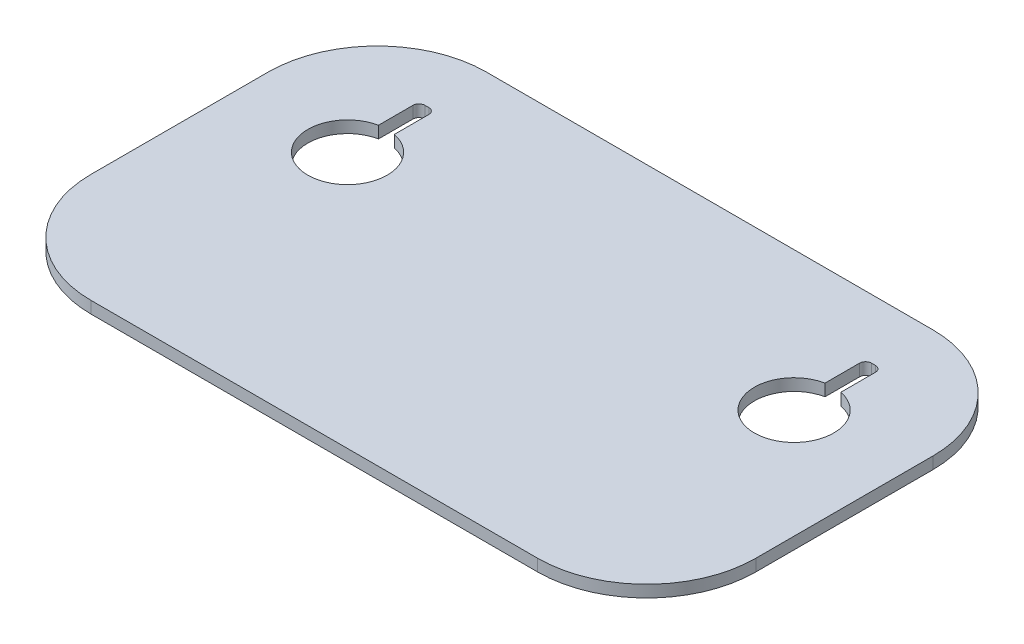
SolidWorks part; units mm, degrees
ref_plane "Front Plane" through (0, 0, 0) normal (0, 0, 1) x (1, 0, 0)
ref_plane "Top Plane" through (0, 0, 0) normal (0, 1, 0) x (1, 0, 0)
ref_plane "Right Plane" through (0, 0, 0) normal (1, 0, 0) x (0, 0, -1)
sketch "Sketch1" plane through (0, 0, 0) normal (0, 1, 0) x (1, 0, 0)
  line L1 (-9.9666, 27.987) -> (215.0634, 27.987)
  line L2 (-64.9666, -27.013) -> (-64.9666, -116.273)
  line L3 (-9.9666, -171.273) -> (215.0634, -171.273)
  line L4 (270.0634, -27.013) -> (270.0634, -116.273)
  arc A0 (-64.9666, -116.273) -> (-9.9666, -171.273) centre (-9.9666, -116.273) ccw
  arc A1 (215.0634, -171.273) -> (270.0634, -116.273) centre (215.0634, -116.273) ccw
  arc A2 (215.0634, 27.987) -> (270.0634, -27.013) centre (215.0634, -27.013) cw
  arc A3 (-9.9666, 27.987) -> (-64.9666, -27.013) centre (-9.9666, -27.013) ccw
  dimension "D3" = 55
extrude "Boss-Extrude1" add sketch "Sketch1" along normal blind 6
sketch "Sketch3" plane through (0, 6, 0) normal (0, 1, 0) x (1, 0, 0)
  line L0 (-9.9666, 53.1042) -> (-9.9666, -2.013) construction
  line L1 (215.0634, 48.0234) -> (215.0634, -218.0505) construction
  line L2 (-64.9666, -27.013) -> (-64.9666, -116.273) construction
  line L3 (270.0634, -116.273) -> (270.0634, -27.013) construction
  line L4 (-115.6589, -42.013) -> (-13.9666, -42.013) construction
  line L5 (215.0634, 27.987) -> (-9.9666, 27.987) construction
  line L6 (10.0334, -42.013) -> (321.2905, -42.013) construction
  line L7 (-10.9666, -2.013) -> (-8.9666, -2.013)
  line L8 (-13.9666, -5.013) -> (-13.9666, -22.4171)
  line L9 (214.0634, -2.013) -> (216.0634, -2.013)
  line L10 (-5.9666, -5.013) -> (-5.9666, -22.4171)
  line L11 (-9.9666, -62.013) -> (-9.9666, -185.9611) construction
  line L12 (211.0634, -5.013) -> (211.0634, -22.4171)
  line L13 (219.0634, -5.013) -> (219.0634, -22.4171)
  arc A0 (-13.9666, -22.4171) -> (-5.9666, -22.4171) centre (-9.9666, -42.013) ccw
  arc A1 (-8.9666, -2.013) -> (-5.9666, -5.013) centre (-8.9666, -5.013) cw
  arc A2 (-10.9666, -2.013) -> (-13.9666, -5.013) centre (-10.9666, -5.013) ccw
  arc A3 (211.0634, -22.4171) -> (219.0634, -22.4171) centre (215.0634, -42.013) ccw
  arc A4 (216.0634, -2.013) -> (219.0634, -5.013) centre (216.0634, -5.013) cw
  arc A5 (214.0634, -2.013) -> (211.0634, -5.013) centre (214.0634, -5.013) ccw
  point P20 (-5.9666, -2.013)
  point P23 (-13.9666, -2.013)
  dimension "D4" = 8
  dimension "D6" = 3
  dimension "D1" = 55
  dimension "D2" = 55
  dimension "D3" = 70
  dimension "D5" = 40
extrude "Cut-Extrude2" cut sketch "Sketch3" against normal blind 280
